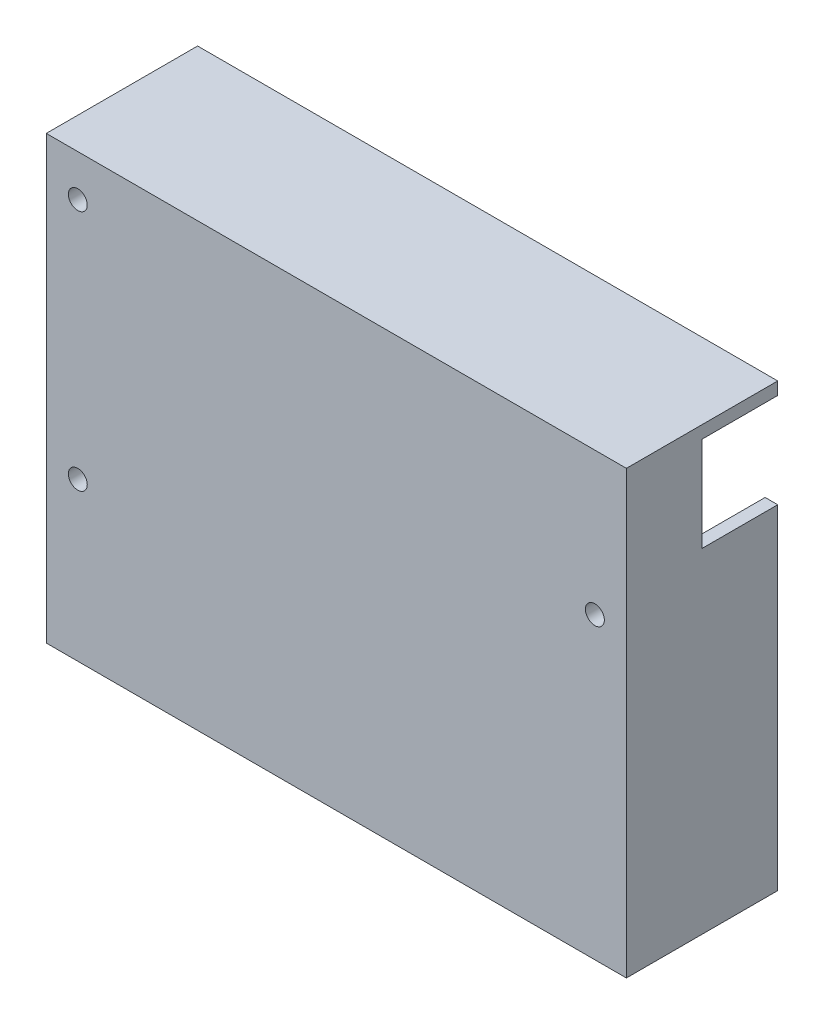
SolidWorks part; units mm, degrees
ref_plane "Front Plane" through (0, 0, 0) normal (0, 0, 1) x (1, 0, 0)
ref_plane "Top Plane" through (0, 0, 0) normal (0, 1, 0) x (1, 0, 0)
ref_plane "Right Plane" through (0, 0, 0) normal (1, 0, 0) x (0, 0, -1)
sketch "Sketch1" plane through (0, 0, 0) normal (0, 0, 1) x (1, 0, 0)
  line L1 (-58.42, 44.45) -> (58.42, 44.45)
  line L2 (-58.42, 44.45) -> (-58.42, -44.45)
  line L3 (-58.42, -44.45) -> (58.42, -44.45)
  line L4 (58.42, 44.45) -> (58.42, -44.45)
  line L5 (-58.42, 44.45) -> (58.42, -44.45) construction
  line L6 (-58.42, -44.45) -> (58.42, 44.45) construction
  point P0 (0, 0)
extrude "Boss-Extrude1" add sketch "Sketch1" along normal blind 30.48
sketch "Sketch2" plane through (0, 0, 0) normal (0, 0, 1) x (1, 0, 0)
  line L0 (-60.96, -19.05) -> (60.96, -19.05)
  line L1 (-60.96, 41.91) -> (60.96, 41.91)
  line L2 (-60.96, 41.91) -> (-60.96, -19.05)
  line L4 (60.96, 41.91) -> (60.96, -19.05)
  line L5 (-60.96, 41.91) -> (27.7091, -19.05) construction
  line L6 (-27.7091, -19.05) -> (60.96, 41.91) construction
  point P0 (0, 0)
  dimension "D1" = 60.96
extrude "Cut-Extrude1" cut sketch "Sketch2" along normal blind 15.24
sketch "Sketch4" plane through (0, 0, 0) normal (0, 0, -1) x (-1, 0, 0)
  line L0 (-58.42, 41.91) -> (58.42, 41.91) construction
  line L1 (-46.482, -8.89) -> (-8.382, -8.89)
  line L2 (-46.482, -8.89) -> (-46.482, -39.37)
  line L3 (-46.482, -39.37) -> (-8.382, -39.37)
  line L4 (-8.382, -8.89) -> (-8.382, -39.37)
  line L5 (-58.42, -44.45) -> (-58.42, -19.05) construction
  dimension "D1" = 11.938
  dimension "D2" = 81.28
extrude "Cut-Extrude2" cut sketch "Sketch4" against normal blind 25.4
sketch "Sketch5" plane through (0, 0, 0) normal (0, 0, -1) x (-1, 0, 0)
  line L0 (60.96, 41.91) -> (60.96, -19.05) construction
  line L1 (60.96, 26.67) -> (71.1101, 26.67)
  line L2 (60.96, 26.67) -> (60.96, 4.6212)
  line L3 (60.96, 4.6212) -> (71.1101, 4.6212)
  line L4 (71.1101, 26.67) -> (71.1101, 4.6212)
  line L5 (-58.42, 41.91) -> (58.42, 41.91) construction
  dimension "D1" = 15.24
sketch "Sketch9" plane through (0, 0, 15.24) normal (0, 0, -1) x (-1, 0, 0)
  line L0 (-46.482, -19.05) -> (-58.42, -19.05) construction
  line L1 (-58.42, 41.91) -> (-55.88, 41.91)
  line L2 (-58.42, 41.91) -> (-58.42, -19.05)
  line L3 (-58.42, -19.05) -> (-55.88, -19.05)
  line L4 (-55.88, 41.91) -> (-55.88, -19.05)
extrude "Boss-Extrude2" add sketch "Sketch9" along normal blind 15.24
sketch "Sketch11" plane through (0, 0, 15.24) normal (0, 0, -1) x (-1, 0, 0)
  line L0 (58.42, -19.05) -> (-8.382, -19.05) construction
  line L1 (58.42, 41.91) -> (55.88, 41.91)
  line L2 (58.42, 41.91) -> (58.42, -19.05)
  line L3 (58.42, -19.05) -> (55.88, -19.05)
  line L4 (55.88, 41.91) -> (55.88, -19.05)
extrude "Boss-Extrude3" add sketch "Sketch11" along normal blind 15.24
sketch "Sketch13" plane through (0, 0, 0) normal (0, 0, -1) x (-1, 0, 0)
  line L0 (55.88, 41.91) -> (55.88, -19.05) construction
  line L1 (55.88, 31.75) -> (62.8135, 31.75)
  line L2 (55.88, 31.75) -> (55.88, -6.35)
  line L3 (55.88, -6.35) -> (62.8135, -6.35)
  line L4 (62.8135, 31.75) -> (62.8135, -6.35)
  dimension "D1" = 10.16
  dimension "D2" = 38.1
extrude "Cut-Extrude6" cut sketch "Sketch13" against normal blind 15.24
sketch "Sketch14" plane through (0, 0, 0) normal (0, 0, -1) x (-1, 0, 0)
  line L1 (-55.88, 41.91) -> (-61.6752, 41.91)
  line L2 (-55.88, 41.91) -> (-55.88, 22.86)
  line L3 (-55.88, 22.86) -> (-61.6752, 22.86)
  line L4 (-61.6752, 41.91) -> (-61.6752, 22.86)
extrude "Cut-Extrude7" cut sketch "Sketch14" against normal blind 15.24
sketch "Sketch15" plane through (0, 0, 15.24) normal (0, 0, -1) x (-1, 0, 0)
  circle A0 centre (52.07, 36.068) radius 1.905
  circle A1 centre (52.07, -12.7) radius 1.905
  circle A2 centre (-52.07, 15.748) radius 1.905
extrude "Cut-Extrude8" cut sketch "Sketch15" against normal blind 48.26
sketch "Sketch16" plane through (0, 0, 0) normal (0, 0, -1) x (-1, 0, 0)
  circle A0 centre (-52.451, -23.8506) radius 1.905
  circle A1 centre (-2.413, -23.8506) radius 1.905
  dimension "D1" = 5.969
  dimension "D2" = 4.8006
  dimension "D3" = 4.8006
  dimension "D4" = 5.969
extrude "Cut-Extrude9" cut sketch "Sketch16" against normal blind 6.858
sketch "Sketch19" plane through (0, 0, 0) normal (0, 0, -1) x (-1, 0, 0)
  line L1 (3.4749, -39.37) -> (55.8876, -39.37)
  line L2 (3.4749, -39.37) -> (3.4749, -22.3454)
  line L3 (3.4749, -22.3454) -> (55.8876, -22.3454)
  line L4 (55.8876, -39.37) -> (55.8876, -22.3454)
extrude "Cut-Extrude10" cut sketch "Sketch19" against normal blind 4.2333
extrude "Cut-Extrude3" cut sketch "Sketch5" against normal blind 15.24
sketch "Sketch6" plane through (0, 0, 0) normal (0, 0, -1) x (-1, 0, 0)
  line L0 (60.96, 41.91) -> (60.96, 26.67) construction
  line L1 (60.96, 29.8635) -> (70.1877, 29.8635)
  line L2 (60.96, 29.8635) -> (60.96, 1.181)
  line L3 (60.96, 1.181) -> (70.1877, 1.181)
  line L4 (70.1877, 29.8635) -> (70.1877, 1.181)
extrude "Cut-Extrude4" cut sketch "Sketch6" against normal blind 15.24
sketch "Sketch7" plane through (0, 0, 0) normal (0, 0, -1) x (-1, 0, 0)
  line L1 (-60.96, 41.91) -> (-68.163, 41.91)
  line L2 (-60.96, 41.91) -> (-60.96, 29.21)
  line L3 (-60.96, 29.21) -> (-68.163, 29.21)
  line L4 (-68.163, 41.91) -> (-68.163, 29.21)
extrude "Cut-Extrude5" cut sketch "Sketch7" against normal blind 15.24
sketch "Sketch8" plane through (0, 0, 15.24) normal (0, 0, -1) x (-1, 0, 0)
  line L1 (-59.2771, 34.1437) -> (57.7024, 34.1437)
  line L2 (-59.2771, 34.1437) -> (-59.2771, -14.1163)
  line L3 (-59.2771, -14.1163) -> (57.7024, -14.1163)
  line L4 (57.7024, 34.1437) -> (57.7024, -14.1163)
  circle A0 centre (57.7024, 34.1437) radius 1.905
  circle A1 centre (57.7024, -14.1163) radius 1.905
  circle A2 centre (-43.8976, 17.6337) radius 1.905
  dimension "D1" = 101.6
